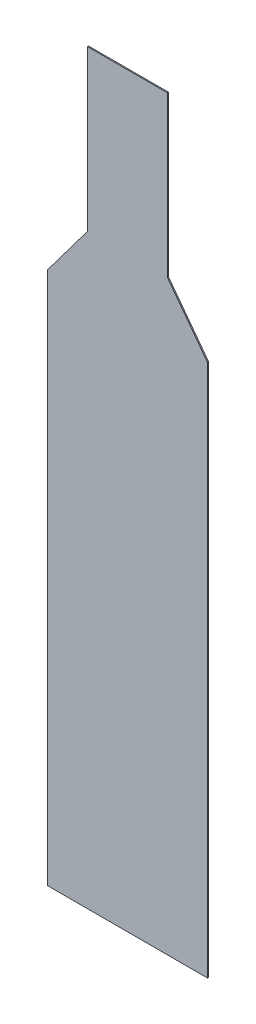
SolidWorks part; units mm, degrees
ref_plane "Front Plane" through (0, 0, 0) normal (0, 0, 1) x (1, 0, 0)
ref_plane "Top Plane" through (0, 0, 0) normal (0, 1, 0) x (1, 0, 0)
ref_plane "Right Plane" through (0, 0, 0) normal (1, 0, 0) x (0, 0, -1)
sketch "Sketch1" plane through (0, 0, 0) normal (0, 0, 1) x (1, 0, 0)
  line L0 (7.5, 0) -> (-7.5, 0)
  line L1 (-7.5, 0) -> (-7.5, 50)
  line L2 (-7.5, 50) -> (-3.75, 55)
  line L3 (-3.75, 55) -> (-3.75, 70)
  line L4 (-3.75, 70) -> (3.75, 70)
  line L5 (3.75, 70) -> (3.75, 55)
  line L6 (3.75, 55) -> (7.5, 50)
  line L7 (7.5, 50) -> (7.5, 0)
  point P4 (0, 0)
  dimension "D1" = 15
  dimension "D2" = 50
  dimension "D3" = 5
  dimension "D4" = 5
  dimension "D5" = 7.5
  dimension "D6" = 70
extrude "Boss-Extrude1" add sketch "Sketch1" along normal blind 0.1 contours L7 L0 L1 L2 L3 L4 L5 L6
